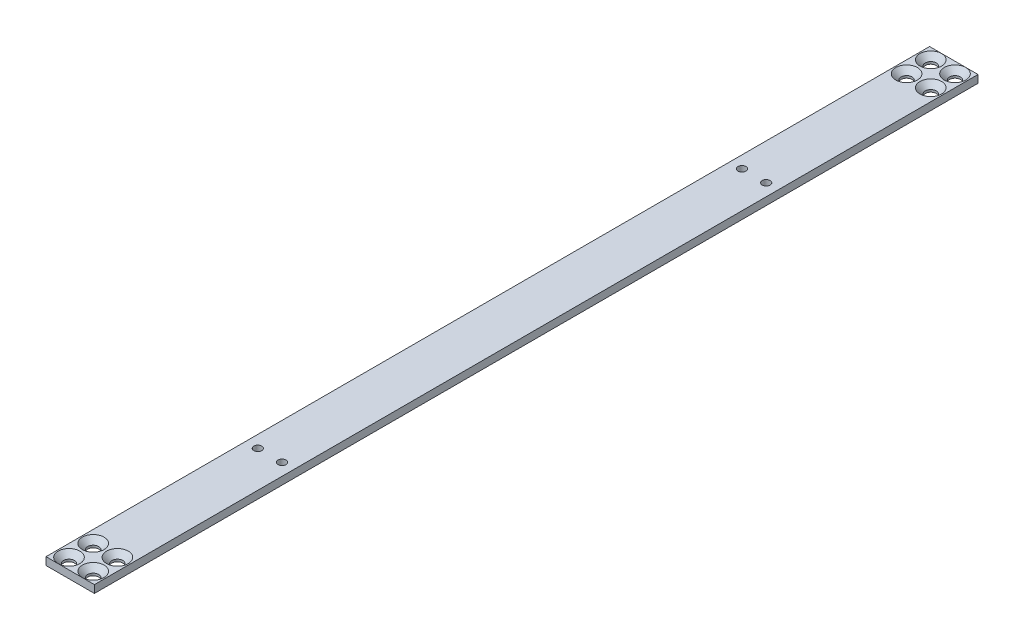
SolidWorks part; units mm, degrees
ref_plane "Front Plane" through (0, 0, 0) normal (0, 0, 1) x (1, 0, 0)
ref_plane "Top Plane" through (0, 0, 0) normal (0, 1, 0) x (1, 0, 0)
ref_plane "Right Plane" through (0, 0, 0) normal (1, 0, 0) x (0, 0, -1)
sketch "Sketch1" plane through (0, 0, 0) normal (0, 1, 0) x (1, 0, 0)
  line L1 (-10, -182.5) -> (10, -182.5)
  line L2 (-10, -182.5) -> (-10, 182.5)
  line L3 (-10, 182.5) -> (10, 182.5)
  line L4 (10, -182.5) -> (10, 182.5)
  line L5 (-10, -182.5) -> (10, 182.5) construction
  line L6 (-10, 182.5) -> (10, -182.5) construction
  point P1 (0, 0)
  dimension "D1" = 365
  dimension "D2" = 20
extrude "Boss-Extrude1" add sketch "Sketch1" along normal blind 3.175
hole_wizard "CSK for M4 SFHCS1" positions "Sketch2" profile "Sketch3" countersink size "M4" standard "ANSI Metric" end condition through all
sketch "Sketch2" plane through (0, 3.175, 0) normal (0, 1, 0) x (1, 0, 0)
  line L1 (-5, -178) -> (5, -178)
  line L2 (-5, -178) -> (-5, -168)
  line L3 (-5, -168) -> (5, -168)
  line L4 (5, -178) -> (5, -168)
  line L5 (-5, -178) -> (5, -168) construction
  line L6 (-5, -168) -> (5, -178) construction
  line L7 (-10, -182.5) -> (10, -182.5) construction
  line L8 (-10, 182.5) -> (-10, -182.5) construction
  line L9 (-55, 0) -> (55, 0) construction
  line L10 (-5, 168) -> (5, 178) construction
  line L11 (-5, 178) -> (5, 168) construction
  line L12 (5, 178) -> (5, 168)
  line L13 (-5, 168) -> (5, 168)
  line L14 (-5, 178) -> (-5, 168)
  line L15 (-5, 178) -> (5, 178)
  point P2 (5, -168)
  point P37 (-5, -178)
  point P38 (-5, -168)
  point P39 (5, -178)
  point P45 (0, -173)
  point P54 (5, 178)
  point P55 (-5, 168)
  point P56 (-5, 178)
  point P57 (5, 168)
  dimension "D1" = 10
  dimension "D2" = 4.5
  dimension "D3" = 10
sketch "Sketch3" plane through (5, 3.175, 168) normal (1, 0, 0) x (0, 0, 1)
  line L0 (0, 0) -> (0, 3.175)
  line L1 (0, 3.175) -> (2.25, 3.175)
  line L2 (2.25, 3.175) -> (2.25, 2.23)
  line L3 (2.25, 2.23) -> (4.48, 0)
  line L5 (4.48, 0) -> (0, 0)
  line L6 (-2.25, 2.23) -> (-4.48, 0) construction
  line L11 (0, -6.35) -> (0, 107.95) construction
  dimension "Thru Hole Dia." = 4.5
  dimension "Thru Hole Depth" = 3.175
  dimension "Near C'Sink Dia." = 8.96
  dimension "Near C'Sink Angle" = 90
hole_wizard "M4x0.7 Tapped Hole1" positions "Sketch4" profile "Sketch6" tap size "M4x0.7" standard "ANSI Metric" end condition through all
sketch "Sketch4" plane through (0, 3.175, 0) normal (0, 1, 0) x (1, 0, 0)
  line L0 (-5, -100) -> (-5, 100)
  line L2 (-10, 182.5) -> (-10, -182.5) construction
  line L3 (0, -55) -> (0, 55) construction
  line L4 (5, -100) -> (5, 100)
  point P1 (-5, -100)
  point P2 (-5, 100)
  point P6 (-5, 0)
  point P18 (5, 100)
  point P19 (5, -100)
  dimension "D1" = 200
  dimension "D2" = 5
sketch "Sketch6" plane through (-5, 3.175, 100) normal (1, 0, 0) x (0, 0, 1)
  line L0 (0, 0) -> (0, 3.175)
  line L1 (0, 3.175) -> (1.65, 3.175)
  line L2 (1.65, 3.175) -> (1.65, 0)
  line L5 (1.65, 0) -> (0, 0)
  line L11 (0, -6.35) -> (0, 107.95) construction
  dimension "Thru Tap Drill Dia." = 3.3
  dimension "Thru Tap Drill Depth" = 3.175
cosmetic thread "Hole Thread1" parameters "D2"=4
cosmetic thread "Hole Thread2" parameters "D2"=4
cosmetic thread "Hole Thread3" parameters "D2"=4
cosmetic thread "Hole Thread4" parameters "D2"=4
